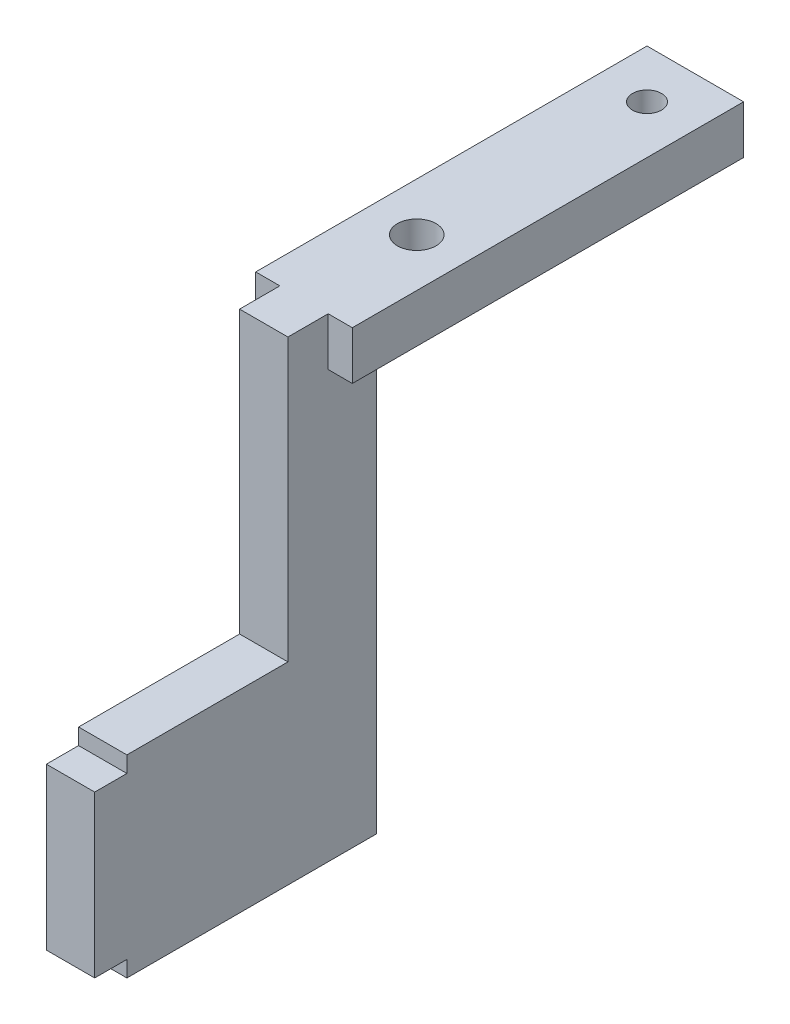
SolidWorks part; units mm, degrees
ref_plane "Front Plane" through (0, 0, 0) normal (0, 0, 1) x (1, 0, 0)
ref_plane "Top Plane" through (0, 0, 0) normal (0, 1, 0) x (1, 0, 0)
ref_plane "Right Plane" through (0, 0, 0) normal (1, 0, 0) x (0, 0, -1)
sketch "Sketch1" plane through (0, 0, 0) normal (0, 0, 1) x (1, 0, 0)
  line L0 (14.8, 20.475) -> (20.8, 20.475)
  line L1 (20.8, 20.475) -> (20.8, 23.475)
  line L2 (20.8, 23.475) -> (14.8, 23.475)
  line L3 (14.8, 23.475) -> (14.8, 20.475)
extrude "Boss-Extrude1" add sketch "Sketch1" along normal blind 24.3 from offset 7.2
sketch "Sketch2" plane through (0, 0, 0) normal (0, 0, 1) x (1, 0, 0)
  line L0 (16.3, -6) -> (19.3, -6)
  line L1 (19.3, -6) -> (19.3, 23.475)
  line L2 (19.3, 23.475) -> (16.3, 23.475)
  line L3 (16.3, 23.475) -> (16.3, -6)
extrude "Boss-Extrude2" add sketch "Sketch2" along normal blind 17.5 from offset 28.5
sketch "Sketch3" plane through (0, 0, 0) normal (0, 1, 0) x (1, 0, 0)
  circle A0 centre (17.8, -24.5) radius 1.2
  circle A1 centre (17.8, -10.2) radius 0.9
extrude "Cut-Extrude1" cut sketch "Sketch3" against normal through all and the other way through all
sketch "Sketch4" plane through (0, 0, 0) normal (1, 0, 0) x (0, 0, -1)
  line L0 (-34, 6) -> (-34, 24.475)
  line L1 (-34, 24.475) -> (-47, 24.475)
  line L2 (-47, 24.475) -> (-47, 6)
  line L3 (-47, 6) -> (-34, 6)
extrude "Cut-Extrude2" cut sketch "Sketch4" against normal through all and the other way through all
sketch "Sketch5" plane through (0, 0, 0) normal (1, 0, 0) x (0, 0, -1)
  line L0 (-44, -7.5) -> (-44, -5)
  line L1 (-44, -5) -> (-47, -5)
  line L2 (-47, -5) -> (-47, -7.5)
  line L3 (-47, -7.5) -> (-44, -7.5)
  line L4 (-44, 5) -> (-44, 7.5)
  line L5 (-44, 7.5) -> (-47, 7.5)
  line L6 (-47, 7.5) -> (-47, 5)
  line L7 (-47, 5) -> (-44, 5)
extrude "Cut-Extrude3" cut sketch "Sketch5" against normal through all and the other way through all
